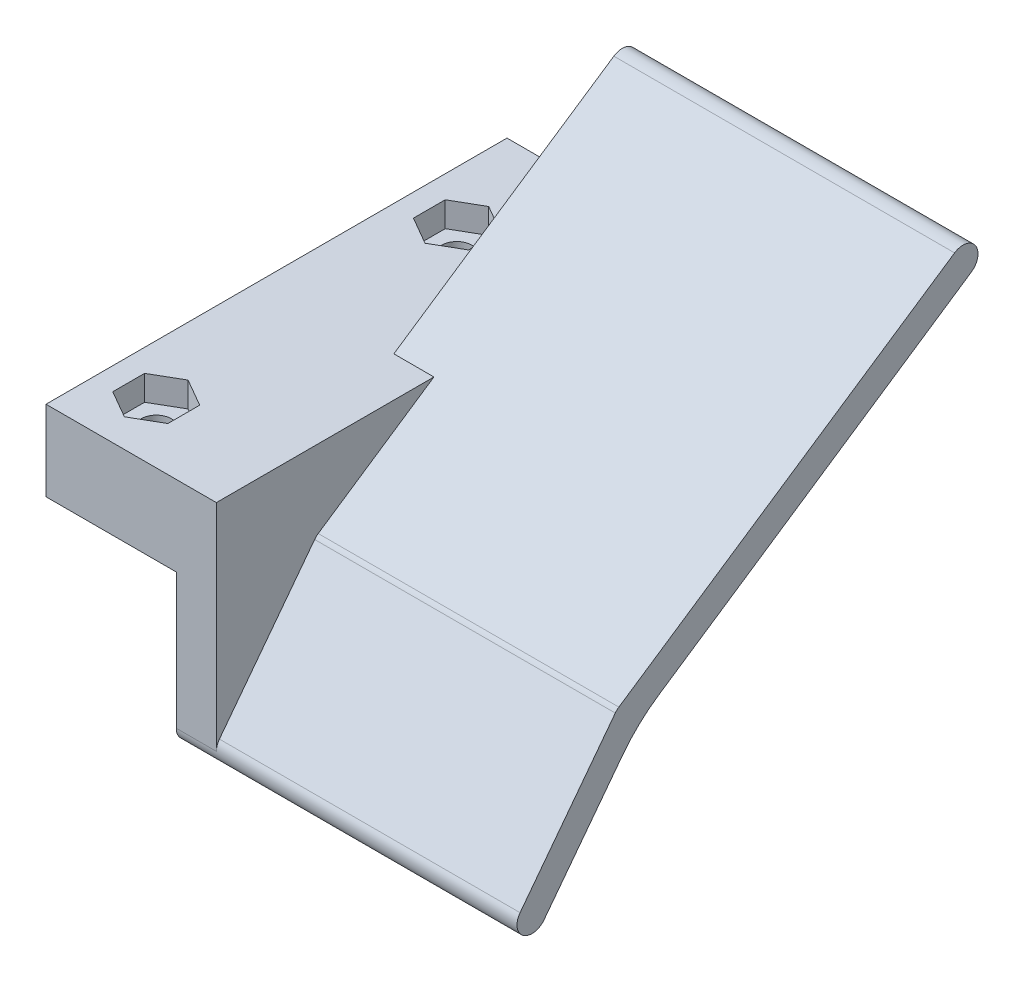
SolidWorks part; units mm, degrees
ref_plane "前视基准面" through (0, 0, 0) normal (0, 0, 1) x (1, 0, 0)
ref_plane "上视基准面" through (0, 0, 0) normal (0, 1, 0) x (1, 0, 0)
ref_plane "右视基准面" through (0, 0, 0) normal (1, 0, 0) x (0, 0, -1)
other "Configuration Table"
sketch "草图1" plane through (0, 0, 0) normal (0, 1, 0) x (1, 0, 0)
  line L0 (0, 0) -> (0, 39.426) construction
  line L1 (56, 0) -> (69, 0)
  line L2 (0, 0) -> (56, 0) construction
  line L3 (0, 0) -> (0, -46) construction
  line L4 (0, -46) -> (56, -46) construction
  line L5 (56, 0) -> (56, -46)
  line L6 (69, 0) -> (69, -46)
  line L7 (69, -46) -> (56, -46)
  line L8 (61, -10) -> (61, -40) construction
  circle A0 centre (61, -10) radius 1.5
  circle A1 centre (61, -40) radius 1.5
  dimension "D4" = 3
  dimension "D5" = 3
  dimension "D1" = 46
  dimension "D2" = 13
  dimension "D3" = 5
  dimension "D6" = 30
  dimension "D7" = 10
  dimension "D8" = 61
extrude "凸台-拉伸1" add sketch "草图1" against normal blind 8
sketch "草图2" plane through (0, 0, 0) normal (0, 1, 0) x (1, 0, 0)
  line L0 (69, -46) -> (69, 0) construction
  line L1 (69, -46) -> (69, 0)
  line L2 (69, 0) -> (73, 0)
  line L3 (73, 0) -> (73, -46)
  line L4 (73, -46) -> (69, -46)
  dimension "D1" = 4
extrude "凸台-拉伸2" add sketch "草图2" along normal blind 15 and the other way blind 23
sketch "草图4" plane through (73, 0, 0) normal (1, 0, 0) x (0, 0, -1)
  line L0 (-1.5, 13.5) -> (-35, -9) construction
  line L1 (0, 15) -> (-1.5, 15) construction
  line L2 (0, 15) -> (0, 13.5) construction
  line L3 (0, 13.5) -> (-1.5, 13.5) construction
  line L4 (0, -23) -> (0, 15)
  line L5 (0, 15) -> (-46, 15)
  line L6 (-46, 15) -> (-46, -23)
  line L7 (-46, -23) -> (0, -23)
  line L8 (0, -23) -> (0, 15) construction
  line L9 (0, 15) -> (-46, 15) construction
  line L10 (-46, 15) -> (-46, -23) construction
  line L11 (-46, -23) -> (0, -23) construction
  line L12 (-1.5, 15) -> (-1.5, 13.5) construction
  line L13 (-46, -23) -> (-44.5, -23) construction
  line L14 (-46, -23) -> (-46, -21.5) construction
  line L15 (-46, -21.5) -> (-44.5, -21.5) construction
  line L16 (-44.5, -23) -> (-44.5, -21.5) construction
  line L19 (-0.6637, 12.2548) -> (-34.1637, -10.2452)
  line L22 (-2.3363, 14.7452) -> (-35.8363, -7.7548)
  line L23 (-35, -9) -> (-44.5, -21.5) construction
  line L24 (-33.8058, -9.9076) -> (-43.3058, -22.4076)
  line L25 (-36.1942, -8.0924) -> (-45.6942, -20.5924)
  arc A4 (-0.6637, 12.2548) -> (-2.3363, 14.7452) centre (-1.5, 13.5) ccw
  arc A5 (-35.8363, -7.7548) -> (-34.1637, -10.2452) centre (-35, -9) ccw
  arc A6 (-33.8058, -9.9076) -> (-36.1942, -8.0924) centre (-35, -9) ccw
  arc A7 (-45.6942, -20.5924) -> (-43.3058, -22.4076) centre (-44.5, -21.5) ccw
  point P10 (-18.25, 2.25)
  point P16 (-39.75, -15.25)
  point P22 (-32.5014, -7.7129)
  point P23 (-34.5151, -8.8558)
  point P26 (-33.862, -12.3934)
  dimension "D8" = 11
  dimension "D9" = 14
  dimension "D6" = 1.5
  dimension "D7" = 1.5
  dimension "D1" = 0
extrude "凸台-拉伸3" add sketch "草图4" along normal blind 30 contours A6 L24 L19 A4 L22 | L24 A6 A5 L19 | L25 A7 L24 L19 A5
sketch "草图5" plane through (73, 0, 0) normal (1, 0, 0) x (0, 0, -1)
  line L0 (0, 13.5) -> (0, 15) construction
  line L1 (0, 15) -> (-1.5, 15) construction
  line L2 (-46, -21.5) -> (-46, -23) construction
  line L3 (-46, -23) -> (-44.5, -23) construction
  line L4 (-46, 0) -> (0, 0) construction
  line L5 (-33.9566, -10.1062) -> (-43.3058, -22.4076) construction
  line L6 (-44.5, -23) -> (0, -23) construction
  line L7 (0, -23) -> (0, 13.5) construction
  line L8 (-2.3363, 14.7452) -> (-35.8363, -7.7548) construction
  line L9 (-46, 0) -> (0, 0) construction
  line L10 (-43.3058, -22.4076) -> (-33.9566, -10.1062) construction
  line L11 (-33.9566, -10.1062) -> (-0.6637, 12.2548) construction
  line L12 (-1.5, 15) -> (-46, 15) construction
  line L13 (-46, 15) -> (-46, -21.5) construction
  line L15 (-35.8363, -7.7548) -> (-2.3363, 14.7452) construction
  line L16 (0, 13.5) -> (0, 15)
  line L17 (0, 15) -> (-1.5, 15)
  line L18 (-46, -21.5) -> (-46, -23)
  line L19 (-46, -23) -> (-44.5, -23)
  line L21 (-33.9566, -10.1062) -> (-43.3058, -22.4076)
  line L22 (-44.5, -23) -> (0, -23)
  line L23 (0, -23) -> (0, -8)
  line L24 (-2.3363, 14.7452) -> (-24.2903, 0)
  line L25 (-24.2903, 0) -> (-46, 0)
  line L26 (-43.3058, -22.4076) -> (-33.9566, -10.1062)
  line L27 (-33.9566, -10.1062) -> (-30.8208, -8)
  line L28 (-1.5, 15) -> (-46, 15)
  line L29 (-46, 15) -> (-46, 0)
  line L31 (-24.2903, 0) -> (-2.3363, 14.7452)
  line L32 (-46, -23) -> (-46, -8) construction
  line L33 (-46, -8) -> (0, -8) construction
  line L34 (0, -8) -> (0, -23) construction
  line L35 (0, -23) -> (-46, -23) construction
  line L37 (-46, 0) -> (-46, 15) construction
  line L38 (-46, 15) -> (0, 15) construction
  line L39 (0, 15) -> (0, 0) construction
  line L40 (-46, -23) -> (-46, -21.5)
  line L41 (-30.8208, -8) -> (0, -8)
  line L42 (0, -8) -> (0, -23)
  line L43 (0, -23) -> (-46, -23)
  line L45 (-46, 0) -> (-46, 15)
  line L46 (-46, 15) -> (0, 15)
  line L47 (0, 15) -> (0, 13.5)
  line L49 (-30.8208, -8) -> (-33.9566, -10.1062)
  arc A0 (0, 13.5) -> (-1.5, 15) centre (-1.5, 13.5) ccw construction
  arc A1 (-46, -21.5) -> (-44.5, -23) centre (-44.5, -21.5) ccw construction
  arc A3 (-44.5, -23) -> (-43.3058, -22.4076) centre (-44.5, -21.5) ccw construction
  arc A5 (-45.6942, -20.5924) -> (-43.3058, -22.4076) centre (-44.5, -21.5) ccw construction
  arc A6 (-0.6637, 12.2548) -> (-2.3363, 14.7452) centre (-1.5, 13.5) ccw construction
  arc A7 (-1.5, 15) -> (-2.3363, 14.7452) centre (-1.5, 13.5) ccw construction
  arc A10 (0, 13.5) -> (-1.5, 15) centre (-1.5, 13.5) ccw
  arc A11 (-46, -21.5) -> (-44.5, -23) centre (-44.5, -21.5) ccw
  arc A13 (-44.5, -23) -> (-43.3058, -22.4076) centre (-44.5, -21.5) ccw
  arc A15 (-46, -21.5) -> (-43.3058, -22.4076) centre (-44.5, -21.5) ccw
  arc A16 (0, 13.5) -> (-2.3363, 14.7452) centre (-1.5, 13.5) ccw
  arc A17 (-1.5, 15) -> (-2.3363, 14.7452) centre (-1.5, 13.5) ccw
  point P14 (-20.7481, 2.905)
  arc M3 (-2.3363, 14.7452) -> (-1.5, 15) centre (-1.5, 13.5) cw
  line M4 (-1.5, 15) -> (-46, 15)
  line M5 (-46, 15) -> (-46, -21.5)
  line M9 (-35.8363, -7.7548) -> (-2.3363, 14.7452)
extrude "切除-拉伸1" cut sketch "草图5" against normal up to next contours L25 M9 M3 M4 M5 | A13 L22 L23 L41 L27 L21 | A11 L18 L19 | A10 L16 L17
fillet "圆角1" radius 15 1 edges at (86, -10.1062, 33.9566)
sketch "草图6" plane through (0, 0, 0) normal (0, 1, 0) x (1, 0, 0)
  line L0 (61, -10) -> (61, -40) construction
  line L1 (63.75, -11.5877) -> (63.75, -8.4123)
  line L2 (63.75, -8.4123) -> (61, -6.8246)
  line L3 (61, -6.8246) -> (58.25, -8.4123)
  line L4 (58.25, -8.4123) -> (58.25, -11.5877)
  line L5 (58.25, -11.5877) -> (61, -13.1754)
  line L6 (61, -13.1754) -> (63.75, -11.5877)
  line L7 (61, -43.1754) -> (63.75, -41.5877)
  line L8 (63.75, -41.5877) -> (63.75, -38.4123)
  line L9 (63.75, -38.4123) -> (61, -36.8246)
  line L10 (61, -36.8246) -> (58.25, -38.4123)
  line L11 (58.25, -38.4123) -> (58.25, -41.5877)
  line L12 (58.25, -41.5877) -> (61, -43.1754)
  circle A0 centre (61, -40) radius 1.5 construction
  circle A1 centre (61, -10) radius 1.5 construction
  circle A2 centre (61, -40) radius 1.5 construction
  circle A3 centre (61, -10) radius 1.5 construction
  circle A4 centre (61, -10) radius 2.75 construction
  circle A5 centre (61, -40) radius 2.75 construction
  point P6 (0, 0)
  dimension "D1" = 5.5
  dimension "D2" = 5.5
extrude "切除-拉伸2" cut sketch "草图6" against normal blind 2.5
